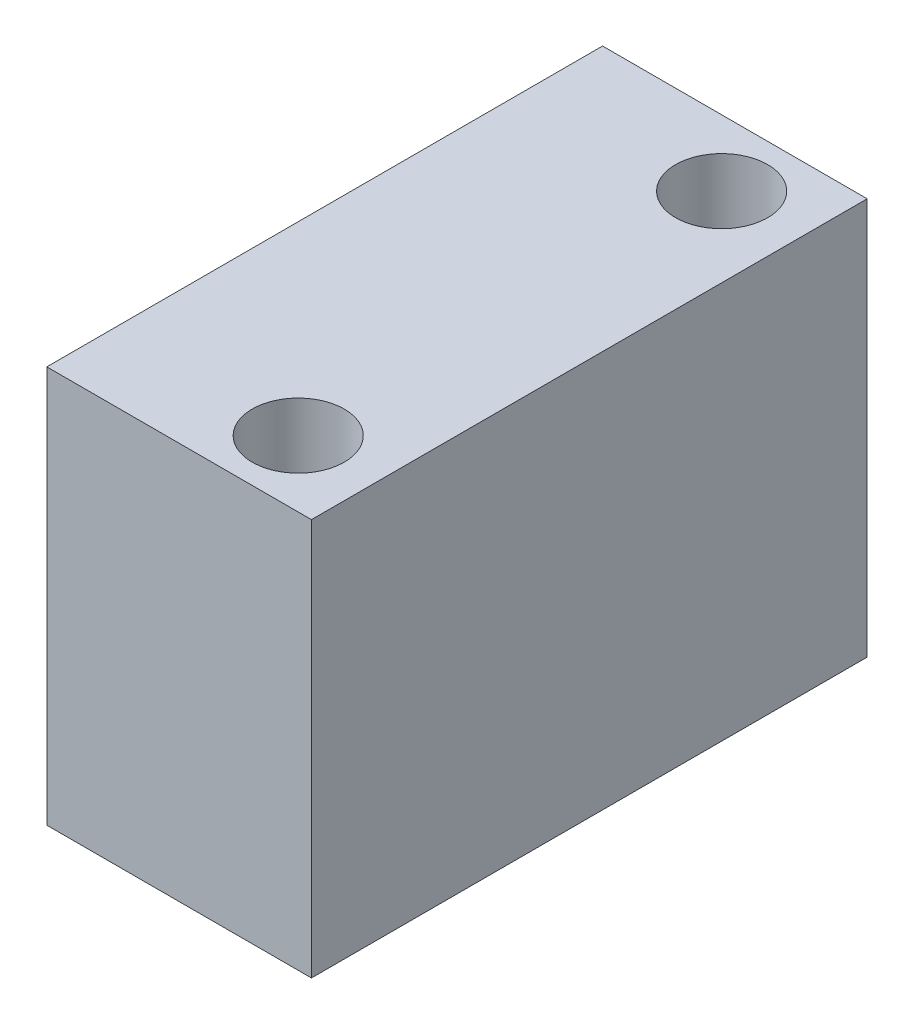
SolidWorks part; units mm, degrees
ref_plane "Front" through (0, 0, 0) normal (0, 0, 1) x (1, 0, 0)
ref_plane "Top" through (0, 0, 0) normal (0, 1, 0) x (1, 0, 0)
ref_plane "Right" through (0, 0, 0) normal (1, 0, 0) x (0, 0, -1)
sketch "Sketch1" plane through (0, 0, 0) normal (0, 1, 0) x (1, 0, 0)
  line L0 (0, 0) -> (0, 5.08)
  line L1 (-1.905, 6.6675) -> (1.905, 6.6675)
  line L2 (-1.905, 6.6675) -> (-1.905, -6.6675)
  line L3 (-1.905, -6.6675) -> (1.905, -6.6675)
  line L4 (1.905, 6.6675) -> (1.905, -6.6675)
  line L5 (-1.905, 6.6675) -> (1.905, -6.6675) construction
  line L6 (-1.905, -6.6675) -> (1.905, 6.6675) construction
  line L7 (0, 0) -> (1.4759, 0)
  circle A0 centre (0, 5.08) radius 1.1049
  circle A1 centre (0, -5.08) radius 1.1049
  point P0 (0, 0)
  dimension "D4" = 2.2098
  dimension "D1" = 13.335
  dimension "D2" = 3.81
  dimension "D3" = 5.08
extrude "Boss-Extrude1" add sketch "Sketch1" along normal blind 9.525
sketch "Sketch2" plane through (0, 9.525, 0) normal (0, 1, 0) x (1, 0, 0)
  line L0 (1.905, 6.6675) -> (1.905, -6.6675) construction
  line L1 (-1.905, 6.6675) -> (-4.445, 6.6675)
  line L2 (-1.905, 6.6675) -> (-1.905, -6.6675)
  line L3 (-1.905, -6.6675) -> (-4.445, -6.6675)
  line L4 (-4.445, 6.6675) -> (-4.445, -6.6675)
  point P7 (-1.905, -6.6675)
  dimension "D1" = 6.35
extrude "Boss-Extrude2" add sketch "Sketch2" against normal blind 9.525
